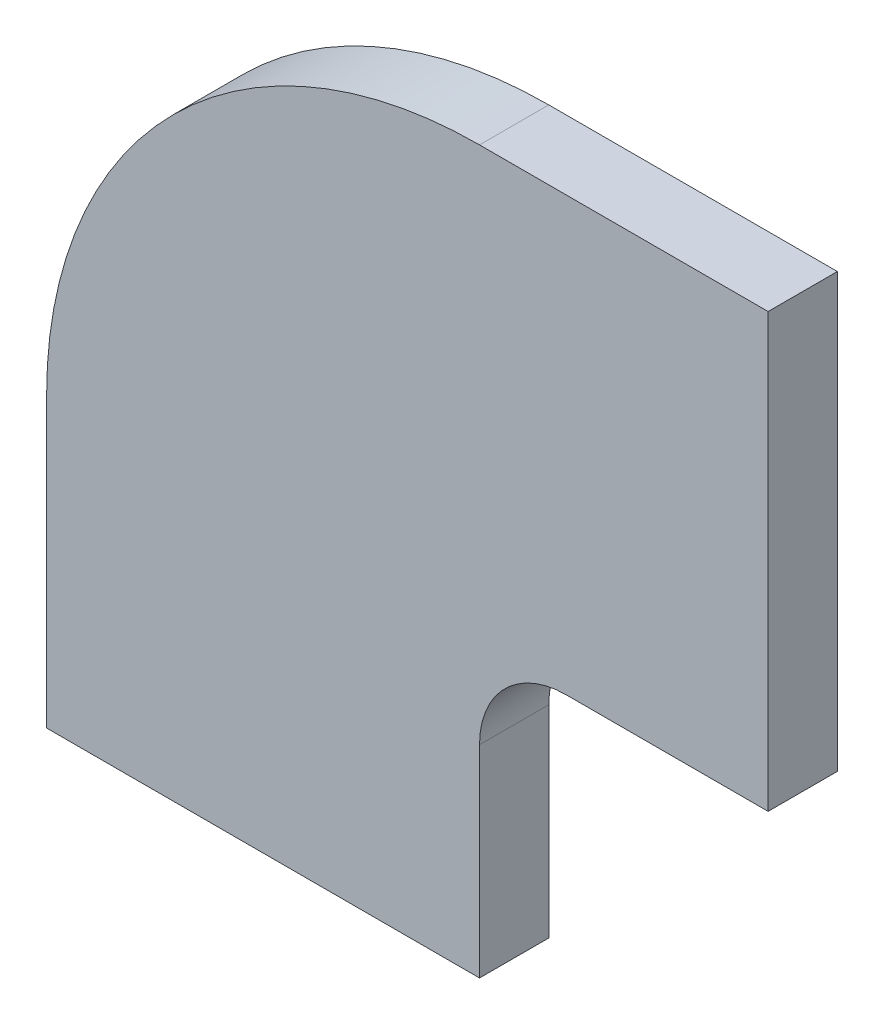
SolidWorks part; units mm, degrees
material "PBT General Purpose"
ref_plane "Front Plane" through (0, 0, 0) normal (0, 0, 1) x (1, 0, 0)
ref_plane "Top Plane" through (0, 0, 0) normal (0, 1, 0) x (1, 0, 0)
ref_plane "Right Plane" through (0, 0, 0) normal (1, 0, 0) x (0, 0, -1)
sketch "Sketch1" plane through (0, 0, 0) normal (0, 0, 1) x (1, 0, 0)
  line L0 (0, 0) -> (0, 1.5)
  line L1 (0, 1.5) -> (-2.5, 1.5)
  line L2 (-2.5, 1.5) -> (-2.5, -1)
  line L3 (-2.5, -1) -> (-1, -1)
  line L4 (-1, -1) -> (-1, 0)
  line L5 (-1, 0) -> (0, 0)
  dimension "D1" = 1.5
  dimension "D2" = 1
  dimension "D3" = 1
  dimension "D4" = 1.5
extrude "Boss-Extrude1" add sketch "Sketch1" along normal mid plane 0.24
fillet "Fillet1" radius 1.5 1 edges at (-2.5, 1.5, 0)
fillet "Fillet2" radius 0.3 1 edges at (-1, 0, 0)
